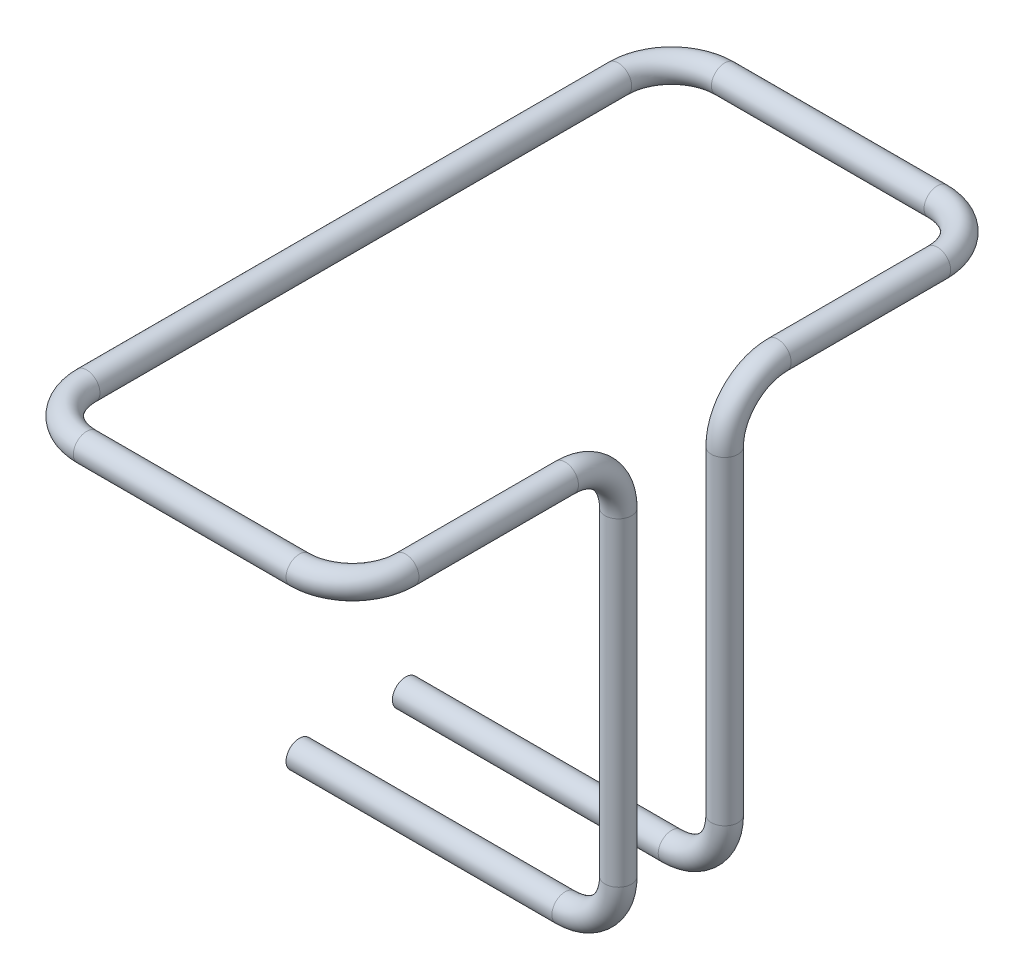
SolidWorks part; units mm, degrees
ref_plane "Front Plane" through (0, 0, 0) normal (0, 0, 1) x (1, 0, 0)
ref_plane "Top Plane" through (0, 0, 0) normal (0, 1, 0) x (1, 0, 0)
ref_plane "Right Plane" through (0, 0, 0) normal (1, 0, 0) x (0, 0, -1)
sketch3d "3DSketch2"
  line L0 (-12.7, 0, 25.4) -> (-76.2, 0, 25.4)
  line L1 (0, 12.7, 0) -> (0, 88.9, 0)
  line L2 (0, 101.6, -12.7) -> (0, 101.6, -50.8)
  line L3 (-12.7, 0, 0) -> (-76.2, 0, 0)
  line L4 (-12.7, 101.6, 88.9) -> (-63.5, 101.6, 88.9)
  line L5 (0, 101.6, 38.1) -> (0, 101.6, 76.2)
  line L6 (-76.2, 101.6, 76.2) -> (-76.2, 101.6, -50.8)
  line L7 (-63.5, 101.6, -63.5) -> (-12.7, 101.6, -63.5)
  line L8 (0, 12.7, 25.4) -> (0, 88.9, 25.4)
  arc A0 (0, 101.6, 76.2) -> (-12.7, 101.6, 88.9) centre (-12.7, 101.6, 76.2) ccw
  arc A1 (-63.5, 101.6, 88.9) -> (-76.2, 101.6, 76.2) centre (-63.5, 101.6, 76.2) ccw
  arc A2 (-76.2, 101.6, -50.8) -> (-63.5, 101.6, -63.5) centre (-63.5, 101.6, -50.8) ccw
  arc A3 (0, 101.6, -50.8) -> (-12.7, 101.6, -63.5) centre (-12.7, 101.6, -50.8) ccw
  arc A4 (0, 88.9, 0) -> (0, 101.6, -12.7) centre (0, 88.9, -12.7) ccw
  arc A5 (0, 88.9, 25.4) -> (0, 101.6, 38.1) centre (0, 88.9, 38.1) ccw
  arc A6 (-12.7, 0, 25.4) -> (0, 12.7, 25.4) centre (-12.7, 12.7, 25.4) ccw
  arc A7 (-12.7, 0, 0) -> (0, 12.7, 0) centre (-12.7, 12.7, 0) ccw
  point P13 (0, 101.6, 88.9)
  point P14 (-12.7, 88.9, 76.2)
  point P17 (-76.2, 101.6, 88.9)
  point P18 (-63.5, 88.9, 76.2)
  point P21 (-76.2, 101.6, -63.5)
  point P22 (-63.5, 88.9, -50.8)
  point P25 (0, 101.6, -63.5)
  point P26 (-12.7, 114.3, -50.8)
  point P29 (0, 101.6, 0)
  point P30 (-12.7, 88.9, -12.7)
  point P33 (0, 101.6, 25.4)
  point P34 (12.7, 88.9, 38.1)
  point P37 (0, 0, 25.4)
  point P38 (-12.7, 12.7, 38.1)
  point P41 (0, 0, 0)
  point P42 (-12.7, 12.7, 12.7)
  dimension "D10" = 12.7
  dimension "D11" = 12.7
  dimension "D12" = 12.7
  dimension "D13" = 12.7
  dimension "D14" = 12.7
  dimension "D15" = 12.7
  dimension "D16" = 12.7
  dimension "D17" = 12.7
  dimension "D1" = 152.4
  dimension "D2" = 76.2
  dimension "D3" = 76.2
  dimension "D4" = 76.2
  dimension "D5" = 76.2
  dimension "D6" = 101.6
  dimension "D7" = 101.6
  dimension "D8" = 63.5
  dimension "D9" = 63.5
sweep "Sweep1" add path "3DSketch2" circular profile diameter 6.35 parameters "D3"=6.35
